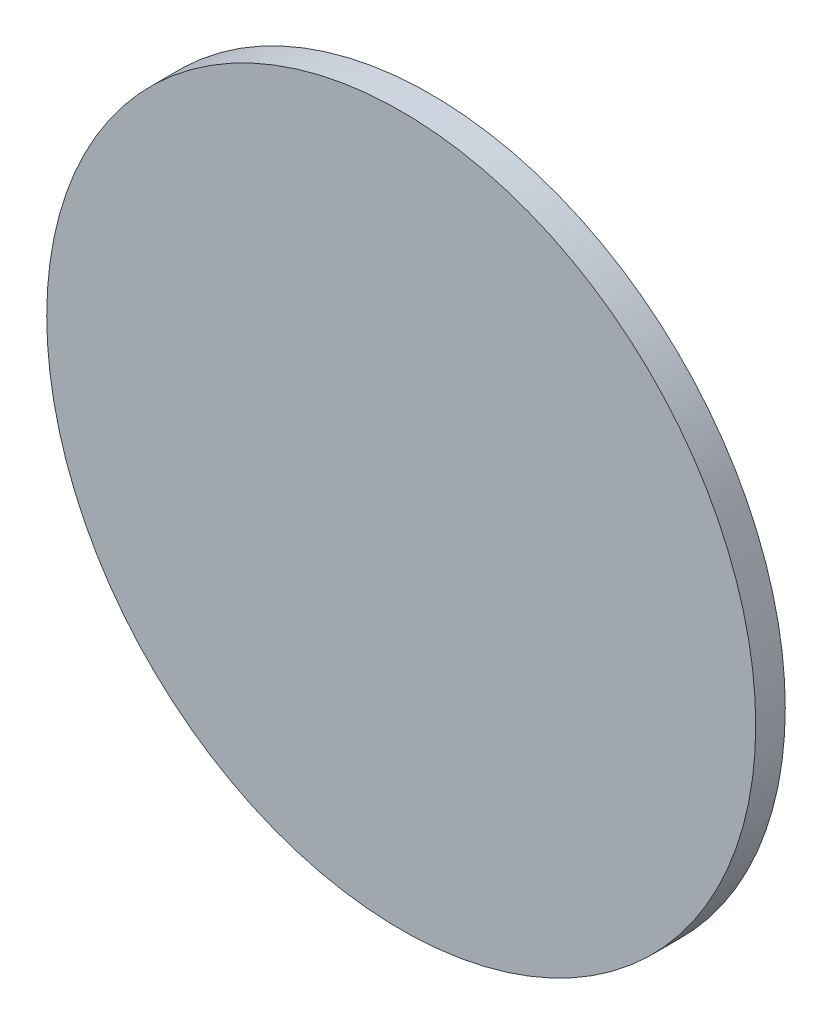
SolidWorks part; units mm, degrees
ref_plane "Plan de face" through (0, 0, 0) normal (0, 0, 1) x (1, 0, 0)
ref_plane "Plan de dessus" through (0, 0, 0) normal (0, 1, 0) x (1, 0, 0)
ref_plane "Plan de droite" through (0, 0, 0) normal (1, 0, 0) x (0, 0, -1)
sketch "Esquisse1" plane through (0, 0, 0) normal (0, 0, 1) x (1, 0, 0)
  circle A0 centre (0, 0) radius 76.2
  dimension "D1" = 152.4
extrude "Boss.-Extru.1" add sketch "Esquisse1" along normal blind 6.35
